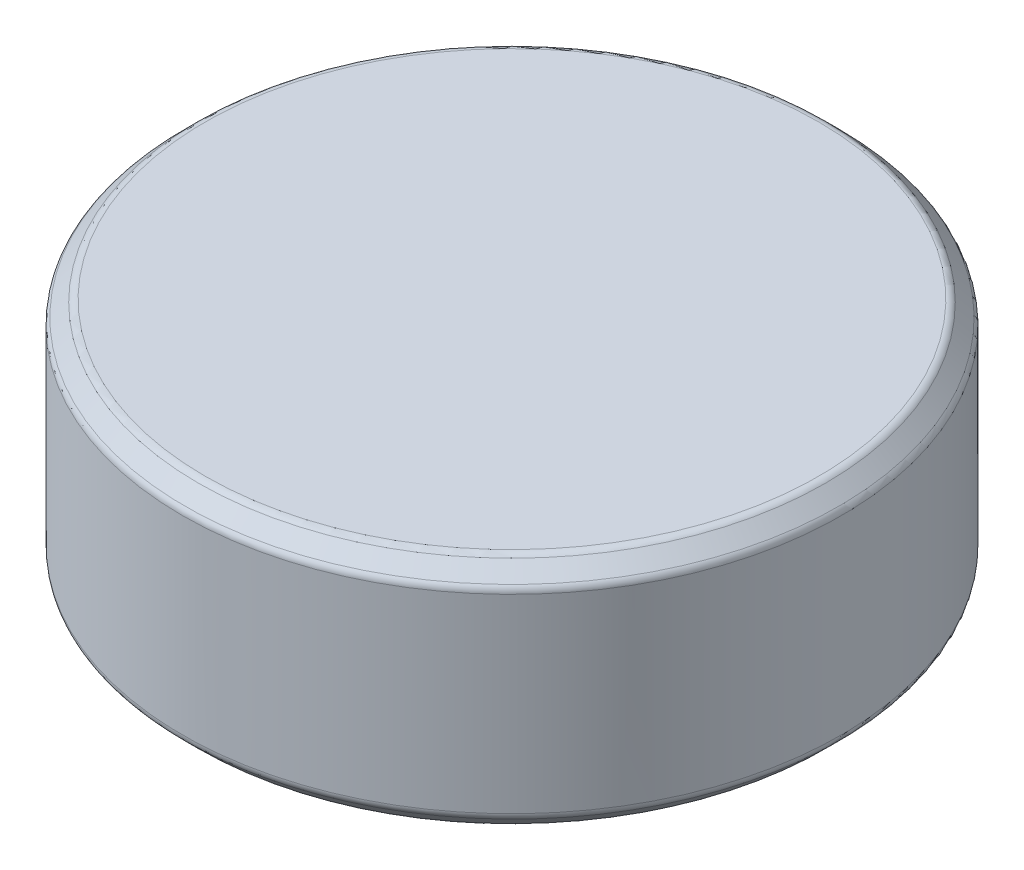
SolidWorks part; units mm, degrees
ref_plane "Front Plane" through (0, 0, 0) normal (0, 0, 1) x (1, 0, 0)
ref_plane "Top Plane" through (0, 0, 0) normal (0, 1, 0) x (1, 0, 0)
ref_plane "Right Plane" through (0, 0, 0) normal (1, 0, 0) x (0, 0, -1)
sketch "Sketch1" plane through (0, 0, 0) normal (0, 1, 0) x (1, 0, 0)
  circle A0 centre (0, 0) radius 35
  dimension "D1" = 70
extrude "Boss-Extrude1" add sketch "Sketch1" along normal blind 25
chamfer "Chamfer1" distance 2 angle 45 2 edges at (0, 0, 35) (0, 25, 35)
fillet "Fillet2" radius 1 4 edges at (0, 0, 33) (0, 2, 35) (0, 23, 35) (0, 25, 33)
